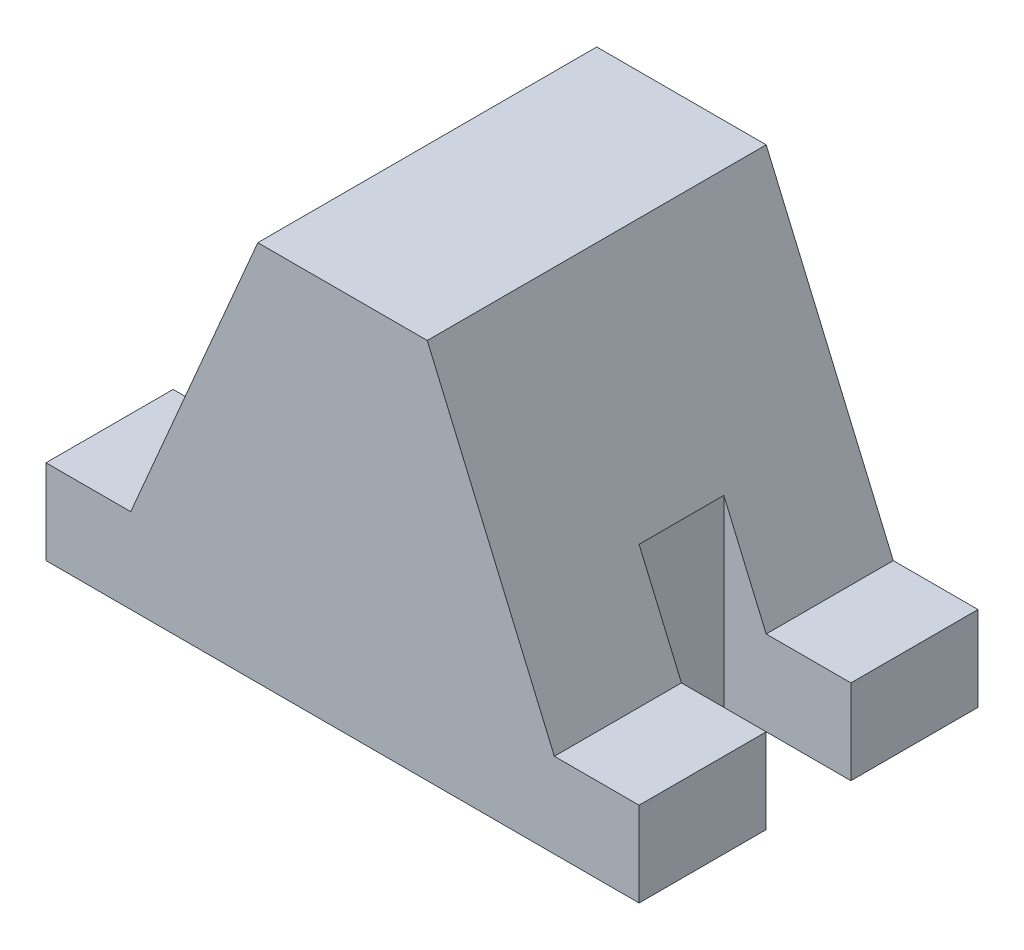
SolidWorks part; units mm, degrees
ref_plane "Alzado" through (0, 0, 0) normal (0, 0, 1) x (1, 0, 0)
ref_plane "Planta" through (0, 0, 0) normal (0, 1, 0) x (1, 0, 0)
ref_plane "Vista lateral" through (0, 0, 0) normal (1, 0, 0) x (0, 0, -1)
sketch "Croquis1" plane through (0, 0, 0) normal (0, 0, 1) x (1, 0, 0)
  line L0 (-35, 0) -> (35, 0)
  line L1 (35, 0) -> (35, 10)
  line L2 (35, 10) -> (25, 10)
  line L3 (25, 10) -> (10, 45)
  line L4 (10, 45) -> (-10, 45)
  line L5 (-10, 45) -> (-25, 10)
  line L6 (-25, 10) -> (-35, 10)
  line L7 (-35, 10) -> (-35, 0)
  point P2 (0, 0)
  point P10 (0, 45)
  dimension "D1" = 70
  dimension "D2" = 50
  dimension "D3" = 20
  dimension "D4" = 45
  dimension "D5" = 10
extrude "Saliente-Extruir1" add sketch "Croquis1" along normal mid plane 40
sketch "Croquis2" plane through (0, 0, 0) normal (0, -1, 0) x (1, 0, 0)
  line L0 (35, 20) -> (35, -20) construction
  line L1 (20, 5) -> (35, 5)
  line L2 (20, 5) -> (20, -5)
  line L3 (20, -5) -> (35, -5)
  line L4 (35, 5) -> (35, -5)
  line L5 (0, -24.9311) -> (0, 26.0956) construction
  line L6 (-35, 5) -> (-35, -5)
  line L7 (-20, -5) -> (-35, -5)
  line L8 (-20, 5) -> (-20, -5)
  line L9 (-20, 5) -> (-35, 5)
  point P4 (35, 0)
  point P7 (35, 0)
  dimension "D1" = 15
  dimension "D2" = 10
extrude "Cortar-Extruir2" cut sketch "Croquis2" against normal up to next
